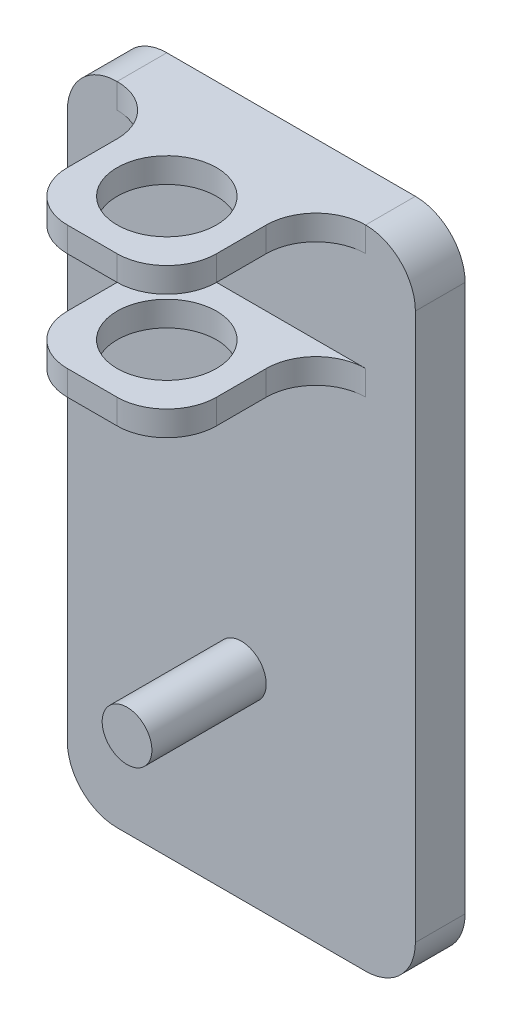
SolidWorks part; units mm, degrees
ref_plane "Alzado" through (0, 0, 0) normal (0, 0, 1) x (1, 0, 0)
ref_plane "Planta" through (0, 0, 0) normal (0, 1, 0) x (1, 0, 0)
ref_plane "Vista lateral" through (0, 0, 0) normal (1, 0, 0) x (0, 0, -1)
sketch "Croquis1" plane through (0, 0, 0) normal (0, 0, 1) x (1, 0, 0)
  line L1 (-35, 65) -> (35, 65)
  line L2 (-35, 65) -> (-35, -65)
  line L3 (-35, -65) -> (35, -65)
  line L4 (35, 65) -> (35, -65)
  line L5 (-35, 65) -> (35, -65) construction
  line L6 (-35, -65) -> (35, 65) construction
  point P0 (0, 0)
  dimension "D1" = 70
  dimension "D2" = 130
extrude "Saliente-Extruir1" add sketch "Croquis1" along normal mid plane 10
fillet "Redondeo1" radius 10 4 edges at (35, -65, 0) (-35, -65, 0) (-35, 65, 0) (35, 65, 0)
sketch "Croquis2" plane through (0, 0, 5) normal (0, 0, 1) x (1, 0, 0)
  line L0 (0, 0) -> (0, -65) construction
  line L1 (-25, -65) -> (25, -65) construction
  circle A0 centre (0, -25) radius 5
  dimension "D1" = 10
  dimension "D2" = 40
extrude "Saliente-Extruir3" add sketch "Croquis2" along normal blind 23
ref_plane "Plano1" through (0, 0, 35) normal (0, 0, 1) x (1, 0, 0)
sketch "Croquis3" plane through (0, 0, 35) normal (0, 0, 1) x (1, 0, 0)
  line L0 (0, 65) -> (0, 0) construction
  line L1 (25, 65) -> (-25, 65) construction
  line L3 (-15, 65) -> (15, 65)
  line L4 (-15, 65) -> (-15, 60)
  line L5 (-15, 60) -> (15, 60)
  line L6 (15, 65) -> (15, 60)
  line L7 (-15, 40) -> (15, 40)
  line L8 (-15, 40) -> (-15, 35)
  line L9 (-15, 35) -> (15, 35)
  line L10 (15, 40) -> (15, 35)
  point P13 (15, 65.4)
  dimension "D1" = 30
  dimension "D2" = 5
  dimension "D3" = 30
extrude "Saliente-Extruir4" add sketch "Croquis3" against normal blind 30
sketch "Croquis4" plane through (0, 65, 0) normal (0, 1, 0) x (1, 0, 0)
  line L0 (0, -35) -> (0, 5) construction
  line L1 (15, -35) -> (-15, -35) construction
  line L2 (25, 5) -> (-25, 5) construction
  line L3 (25, -5) -> (15, -5) construction
  circle A0 centre (0, -20) radius 10
  dimension "D1" = 20
  dimension "D2" = 15
sketch "Croquis5" plane through (0, 35, 0) normal (0, -1, 0) x (1, 0, 0)
  line L0 (-15, 35) -> (15, 35) construction
  circle A0 centre (0, 20) radius 10
  point P4 (0, 20)
  dimension "D2" = 20
  dimension "D1" = 15
extrude "Cortar-Extruir2" cut sketch "Croquis5" along direction (0, -1, 0) on the side against the normal through all
fillet "Redondeo2" radius 10 4 edges at (-15, 62.5, 5) (-15, 62.5, 35) (15, 62.5, 5) (15, 62.5, 35)
fillet "Redondeo3" radius 10 4 edges at (-15, 37.5, 5) (-15, 37.5, 35) (15, 37.5, 5) (15, 37.5, 35)
